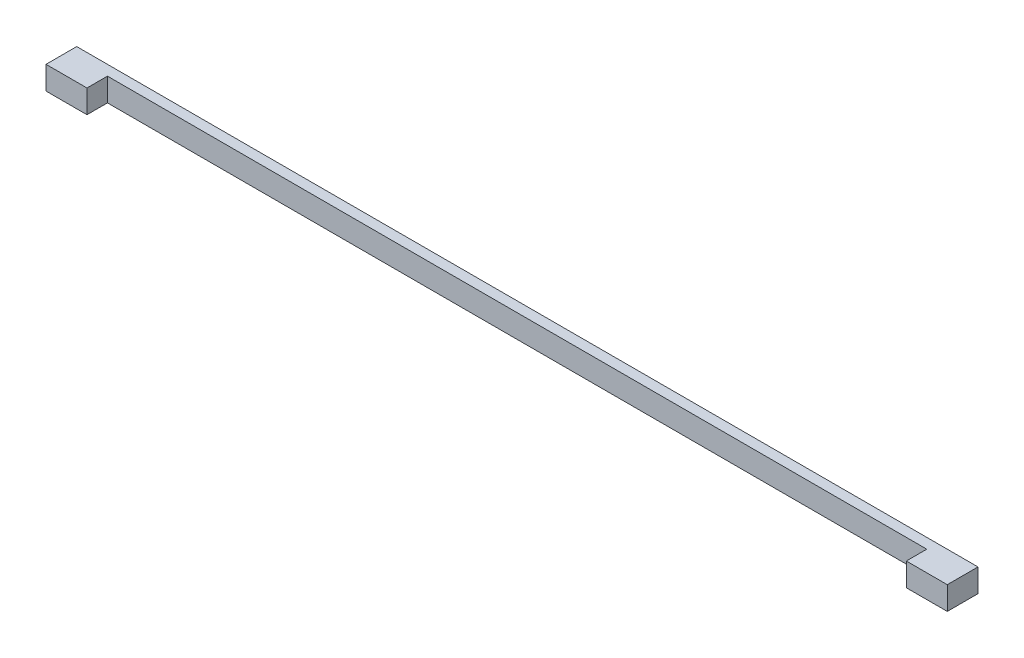
SolidWorks part; units mm, degrees
ref_plane "정면" through (0, 0, 0) normal (0, 0, 1) x (1, 0, 0)
ref_plane "윗면" through (0, 0, 0) normal (0, 1, 0) x (1, 0, 0)
ref_plane "우측면" through (0, 0, 0) normal (1, 0, 0) x (0, 0, -1)
sketch "스케치1" plane through (0, 0, 0) normal (0, 0, 1) x (1, 0, 0)
  line L1 (-220, 5.6601) -> (220, 5.6601)
  line L2 (-220, 5.6601) -> (-220, -5.6601)
  line L3 (-220, -5.6601) -> (220, -5.6601)
  line L4 (220, 5.6601) -> (220, -5.6601)
  line L5 (-220, 5.6601) -> (220, -5.6601) construction
  line L6 (-220, -5.6601) -> (220, 5.6601) construction
  point P0 (0, 0)
  dimension "D1" = 440
extrude "보스-돌출1" add sketch "스케치1" along normal blind 5
sketch "스케치2" plane through (0, 0, 5) normal (0, 0, 1) x (1, 0, 0)
  line L0 (220, 5.6601) -> (-220, 5.6601) construction
  line L1 (-220, -5.6601) -> (-200, -5.6601)
  line L2 (-220, -5.6601) -> (-220, 5.6601)
  line L3 (-220, 5.6601) -> (-200, 5.6601)
  line L4 (-200, -5.6601) -> (-200, 5.6601)
  line L5 (-220, -5.6601) -> (220, -5.6601) construction
  line L6 (220, 5.6601) -> (200, 5.6601)
  line L7 (220, 5.6601) -> (220, -5.6601)
  line L8 (220, -5.6601) -> (200, -5.6601)
  line L9 (200, 5.6601) -> (200, -5.6601)
  dimension "D1" = 20
  dimension "D2" = 20
extrude "보스-돌출2" add sketch "스케치2" along normal blind 10
